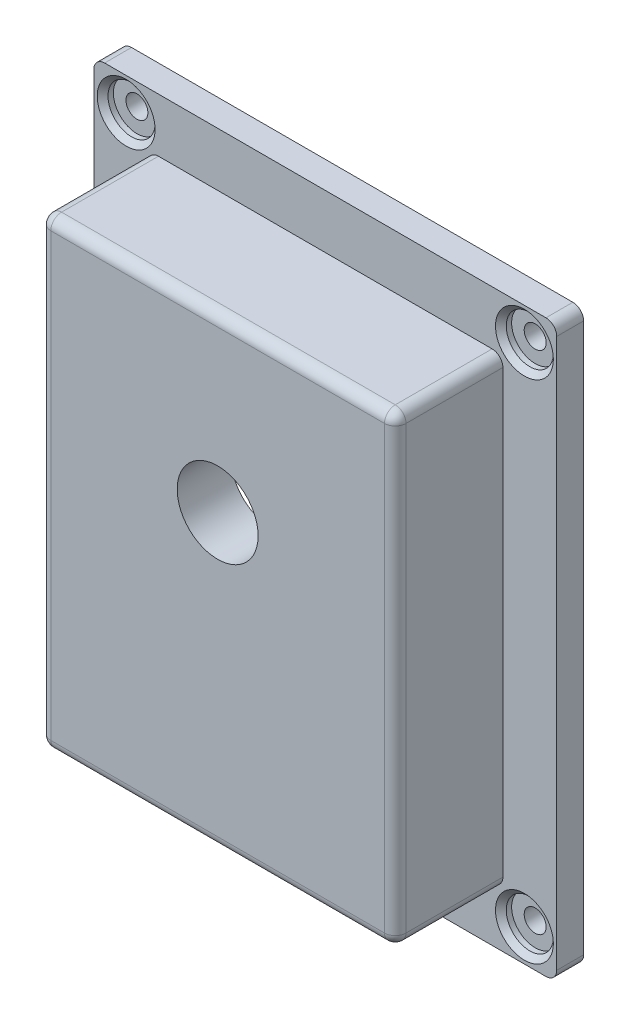
SolidWorks part; units mm, degrees
ref_plane "Front Plane" through (0, 0, 0) normal (1, 0, 0) x (0, 1, 0)
ref_plane "Top Plane" through (0, 0, 0) normal (0, 0, 1) x (0, 1, 0)
ref_plane "Right Plane" through (0, 0, 0) normal (0, 1, 0) x (-1, 0, 0)
sketch "Sketch2" plane through (0, 0, 0) normal (0, 0, 1) x (0, 1, 0)
  line L1 (0, 0) -> (41.91, 0)
  line L2 (0, 0) -> (0, 29.21)
  line L3 (0, 29.21) -> (41.91, 29.21)
  line L4 (41.91, 0) -> (41.91, 29.21)
  line L5 (-6.35, -6.35) -> (48.26, -6.35)
  line L6 (-6.35, -6.35) -> (-6.35, 35.56)
  line L7 (-6.35, 35.56) -> (48.26, 35.56)
  line L8 (48.26, -6.35) -> (48.26, 35.56)
  dimension "D1" = 29.21
  dimension "D2" = 41.91
  dimension "D3" = 6.35
  dimension "D4" = 6.35
  dimension "D6" = 6.35
  dimension "D5" = 6.35
extrude "Boss-Extrude1" add sketch "Sketch2" along normal blind 9.525
sketch "Sketch4" plane through (0, 0, 9.525) normal (0, 0, 1) x (1, 0, 0)
  line L1 (-35.56, 48.26) -> (6.35, 48.26)
  line L2 (-35.56, 48.26) -> (-35.56, -6.35)
  line L3 (-35.56, -6.35) -> (6.35, -6.35)
  line L4 (6.35, 48.26) -> (6.35, -6.35)
extrude "Boss-Extrude2" add sketch "Sketch4" along normal blind 6.35
sketch "Sketch6" plane through (0, 0, 15.875) normal (0, 0, 1) x (1, 0, 0)
  line L0 (6.35, 48.26) -> (-35.56, 48.26) construction
  circle A0 centre (-14.605, 28.0416) radius 4.7752
  point P2 (-14.605, 48.26)
  dimension "D2" = 9.5504
  dimension "D1" = 20.2184
extrude "Cut-Extrude1" cut sketch "Sketch6" against normal through all
sketch "Sketch7" plane through (0, 0, 0) normal (0, 0, 1) x (0, 1, 0)
  line L1 (-6.35, -6.35) -> (48.26, -6.35)
  line L2 (-6.35, -6.35) -> (-6.35, 35.56)
  line L3 (-6.35, 35.56) -> (48.26, 35.56)
  line L4 (48.26, -6.35) -> (48.26, 35.56)
  line L5 (-12.7, -12.7) -> (54.61, -12.7)
  line L6 (-12.7, -12.7) -> (-12.7, 41.91)
  line L7 (-12.7, 41.91) -> (54.61, 41.91)
  line L8 (54.61, -12.7) -> (54.61, 41.91)
  dimension "D3" = 6.35
  dimension "D4" = 6.35
  dimension "D1" = 6.35
  dimension "D2" = 6.35
extrude "Boss-Extrude3" add sketch "Sketch7" along normal blind 3.175
sketch "Sketch8" plane through (0, 0, 3.175) normal (0, 0, 1) x (1, 0, 0)
  line L0 (-35.56, 48.26) -> (-35.56, -6.35) construction
  line L1 (6.35, 48.26) -> (-35.56, 48.26) construction
  line L2 (6.35, -6.35) -> (6.35, 48.26) construction
  line L3 (-35.56, -6.35) -> (6.35, -6.35) construction
  point P0 (-38.1, 50.8)
  point P1 (8.89, 50.8)
  point P2 (8.89, -8.89)
  point P3 (-38.1, -8.89)
  dimension "D1" = 2.54
  dimension "D2" = 2.54
  dimension "D3" = 2.54
  dimension "D4" = 2.54
hole_wizard "CBORE for #2 Binding Head Machine Screw1" positions "Sketch8" profile "Sketch9" counterbore size "#2" standard "ANSI Inch" end condition through all
sketch "Sketch9" plane through (-38.1, 50.8, 3.175) normal (1, 0, 0) x (0, -1, 0)
  line L0 (0, 0) -> (0, 3.175)
  line L1 (0, 3.175) -> (1.2954, 3.175)
  line L3 (1.2954, 3.175) -> (1.2954, 1.27)
  line L4 (2.7788, 1.27) -> (1.2954, 1.27)
  line L5 (2.7788, 1.27) -> (2.7788, 0.635)
  line L6 (2.7788, 0.635) -> (3.4138, 0)
  line L7 (3.4138, 0) -> (0, 0)
  line L8 (-2.7788, 0.635) -> (-3.4138, 0) construction
  line L11 (0, -6.35) -> (0, 107.95) construction
  dimension "Thru Hole Dia." = 2.5908
  dimension "Thru Hole Depth" = 3.175
  dimension "C'Bore Dia." = 5.5575
  dimension "C'Bore Depth" = 1.27
  dimension "Near C'Sink Dia." = 6.8275
  dimension "Near C'Sink Angle" = 90
fillet "Fillet1" radius 1.27 12 edges at (-41.91, 54.61, 1.5875) (12.7, 54.61, 1.5875) (12.7, -12.7, 1.5875) (-41.91, -12.7, 1.5875) (6.35, 48.26, 9.525) (-35.56, 48.26, 9.525) (-14.605, 48.26, 15.875) (-35.56, 20.955, 15.875) (6.35, 20.955, 15.875) (-14.605, -6.35, 15.875) (6.35, -6.35, 9.525) (-35.56, -6.35, 9.525)
equation "\"THICKNESS_WALL\"=0.25"
equation "\"D3@Sketch2\"=\"THICKNESS_WALL\""
equation "\"D4@Sketch2\"=\"THICKNESS_WALL\""
equation "\"D6@Sketch2\"=\"THICKNESS_WALL\""
equation "\"D5@Sketch2\"=\"THICKNESS_WALL\""
equation "\"MAX_GEAR_HEIGHT\"= 0.375"
equation "\"D1@Boss-Extrude1\"=\"MAX_GEAR_HEIGHT\""
equation "\"D1@Boss-Extrude2\"=\"THICKNESS_WALL\""
equation "\"LARGE_GEAR_DIA\"= 1.042"
equation "\"D1@Sketch6\"=(\"LARGE_GEAR_DIA\" + \"CLEARANCE\")/2"
equation "\"CLEARANCE\"= 0.55"
equation "\"D1@Sketch7\"=\"THICKNESS_WALL\""
equation "\"D2@Sketch7\"=\"THICKNESS_WALL\""
equation "\"D3@Sketch7\"=\"THICKNESS_WALL\""
equation "\"D4@Sketch7\"=\"THICKNESS_WALL\""
equation "\"D1@Boss-Extrude3\"=\"THICKNESS_WALL\"/2"
equation "\"D1@Sketch8\"=\"THICKNESS_WALL\"/2.5"
equation "\"D2@Sketch8\"=\"THICKNESS_WALL\"/2.5"
equation "\"D3@Sketch8\"=\"THICKNESS_WALL\"/2.5"
equation "\"D4@Sketch8\"=\"THICKNESS_WALL\"/2.5"
equation "\"GEAR_BEARING_DIA\"= 0.376"
equation "\"D2@Sketch6\"=\"GEAR_BEARING_DIA\""
equation "\"SMALL_GEAR_DIA\"= 0.417"
equation "\"SMALL_BEARING_DIA\"= 0.252"
